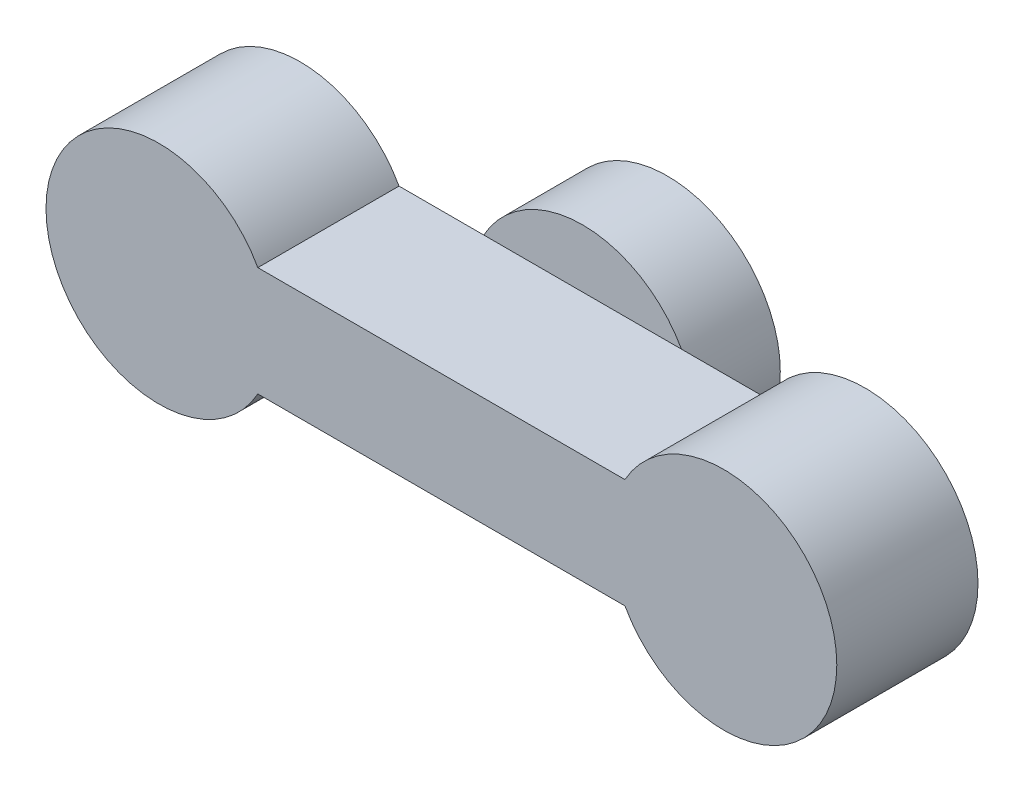
SolidWorks part; units mm, degrees
ref_plane "Front Plane" through (0, 0, 0) normal (0, 0, 1) x (1, 0, 0)
ref_plane "Top Plane" through (0, 0, 0) normal (0, 1, 0) x (1, 0, 0)
ref_plane "Right Plane" through (0, 0, 0) normal (1, 0, 0) x (0, 0, -1)
sketch "Sketch1" plane through (0, 0, 0) normal (0, 0, 1) x (1, 0, 0)
  circle A0 centre (0, 0) radius 1
  circle A1 centre (0, 0) radius 2
extrude "Boss-Extrude1" add sketch "Sketch1" along normal blind 1
sketch "Sketch2" plane through (0, 0, 1) normal (0, 0, 1) x (1, 0, 0)
  circle A1 centre (0, 0) radius 2
extrude "Boss-Extrude2" add sketch "Sketch2" along normal blind 0.5
sketch "Sketch3" plane through (0, 0, 1.5) normal (0, 0, 1) x (1, 0, 0)
  line L2 (3.25, -0.9682) -> (-3.25, -0.9682)
  line L4 (3.25, 0.9682) -> (-3.25, 0.9682)
  arc A0 (-3.25, 0.9682) -> (-3.25, -0.9682) centre (-5, 0) ccw
  arc A1 (3.25, -0.9682) -> (3.25, 0.9682) centre (5, 0) ccw
  point P3 (0, 0)
  point P5 (0, 0)
  dimension "D1" = 4
  dimension "D2" = 4
  dimension "D3" = 6.5
  dimension "D4" = 10
extrude "Boss-Extrude3" add sketch "Sketch3" along normal blind 2.5
